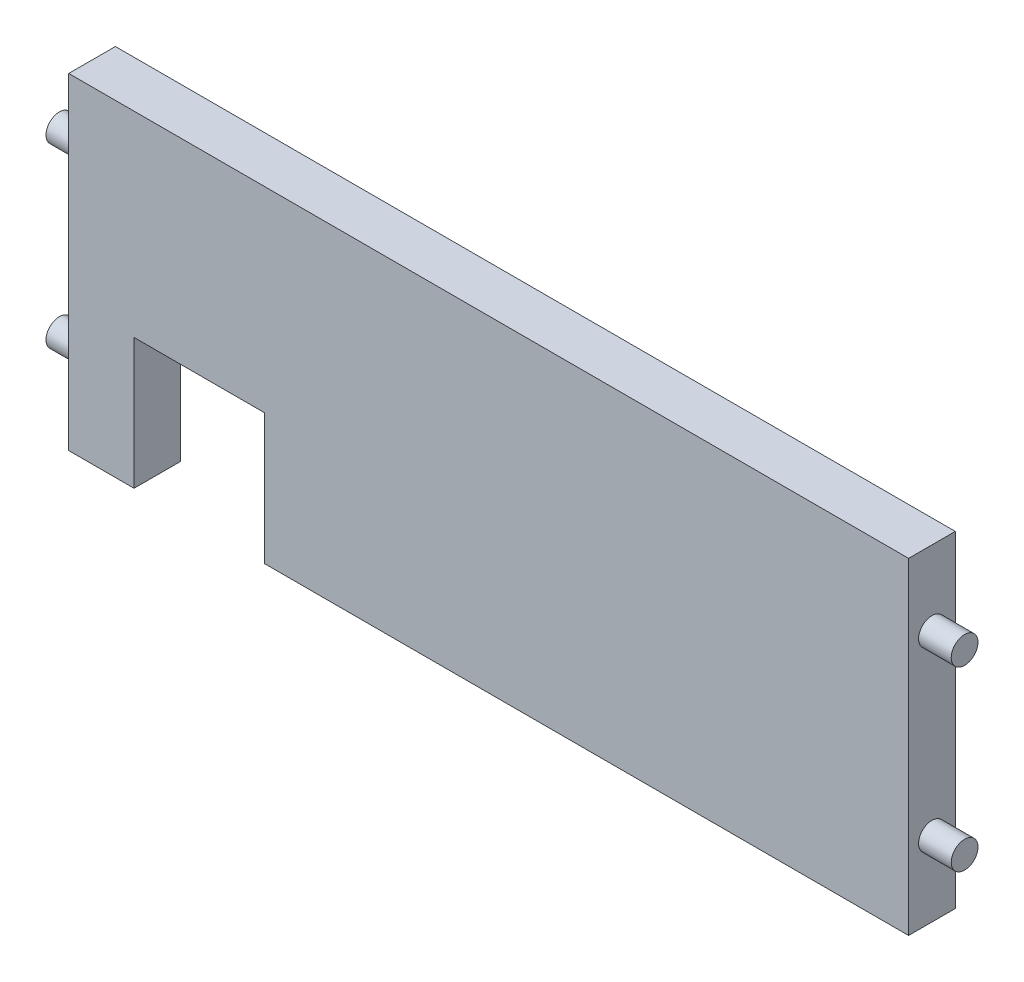
SolidWorks part; units mm, degrees
ref_plane "Front Plane" through (0, 0, 0) normal (0, 0, 1) x (1, 0, 0)
ref_plane "Top Plane" through (0, 0, 0) normal (0, 1, 0) x (1, 0, 0)
ref_plane "Right Plane" through (0, 0, 0) normal (1, 0, 0) x (0, 0, -1)
sketch "Sketch1" plane through (0, 0, 0) normal (0, 0, 1) x (1, 0, 0)
  line L0 (-45, -17.5) -> (-38, -17.5) construction
  line L1 (-45, -17.5) -> (45, -17.5)
  line L2 (-45, -17.5) -> (-45, 17.5)
  line L3 (-45, 17.5) -> (45, 17.5)
  line L4 (45, -17.5) -> (45, 17.5)
  line L5 (-45, -17.5) -> (45, 17.5) construction
  line L6 (-45, 17.5) -> (45, -17.5) construction
  line L7 (-24, -17.5) -> (-5, -17.5) construction
  line L8 (-38, -17.5) -> (-24, -17.5)
  line L9 (-38, -17.5) -> (-38, -3.5)
  line L10 (-38, -3.5) -> (-24, -3.5)
  line L11 (-24, -17.5) -> (-24, -3.5)
  line L13 (-5, -17.5) -> (5, -17.5)
  line L23 (-5, -17.5) -> (5, -17.5)
  point P0 (0, 0)
  dimension "D1" = 90
  dimension "D2" = 35
  dimension "D3" = 7
  dimension "D4" = 14
  dimension "D5" = 14
  dimension "D6" = 19
  dimension "D7" = 10
extrude "Boss-Extrude1" add sketch "Sketch1" along normal blind 5
sketch "Sketch2" plane through (45, 0, 0) normal (1, 0, 0) x (0, 0, -1)
  line L0 (-2.5, 17.5) -> (-2.5, 9.5) construction
  line L1 (-5, 17.5) -> (0, 17.5) construction
  line L2 (55, 0) -> (-55, 0) construction
  circle A0 centre (-2.5, 9.5) radius 1.435
  circle A1 centre (-2.5, -9.5) radius 1.435
  dimension "D2" = 2.87
  dimension "D1" = 8
extrude "Boss-Extrude2" add sketch "Sketch2" along normal blind 3.5
sketch "Sketch3" plane through (-45, 0, 0) normal (-1, 0, 0) x (0, 0, 1)
  line L0 (2.5, 17.5) -> (2.5, 9.5) construction
  line L1 (5, 17.5) -> (0, 17.5) construction
  line L2 (55, 0) -> (-55, 0) construction
  circle A0 centre (2.5, 9.5) radius 1.435
  circle A1 centre (2.5, -9.5) radius 1.435
  dimension "D2" = 2.87
  dimension "D1" = 8
extrude "Boss-Extrude3" add sketch "Sketch3" along normal blind 3.5
